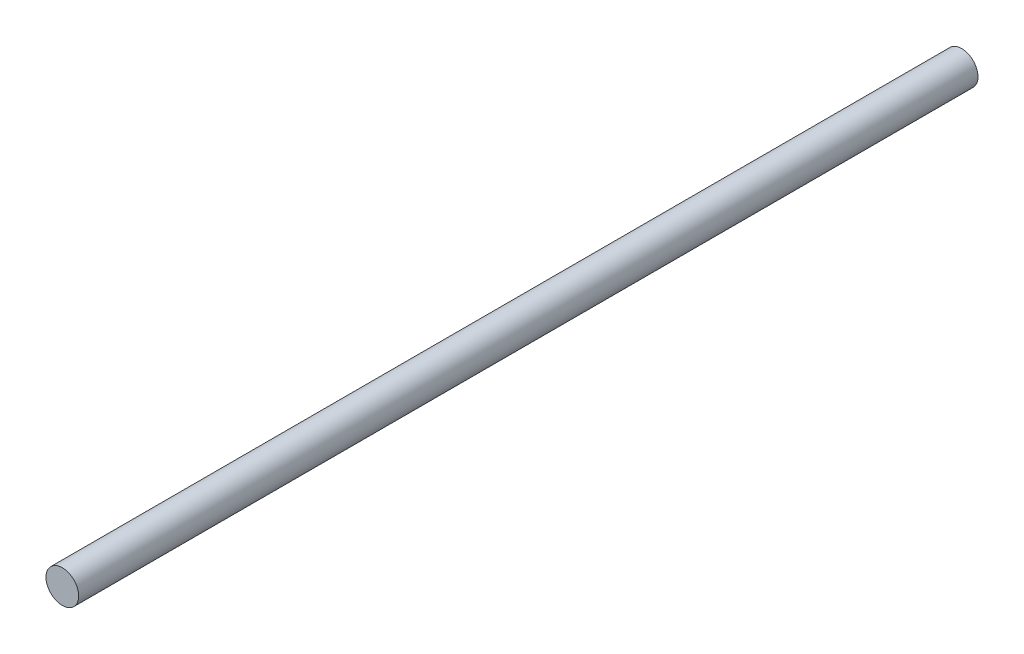
SolidWorks part; units mm, degrees
ref_plane "Front Plane" through (0, 0, 0) normal (0, 0, 1) x (1, 0, 0)
ref_plane "Top Plane" through (0, 0, 0) normal (0, 1, 0) x (1, 0, 0)
ref_plane "Right Plane" through (0, 0, 0) normal (1, 0, 0) x (0, 0, -1)
sketch "Sketch1" plane through (0, 0, 0) normal (0, 0, 1) x (1, 0, 0)
  circle A0 centre (0, 0) radius 4
extrude "Boss-Extrude1" add sketch "Sketch1" along normal blind 220
